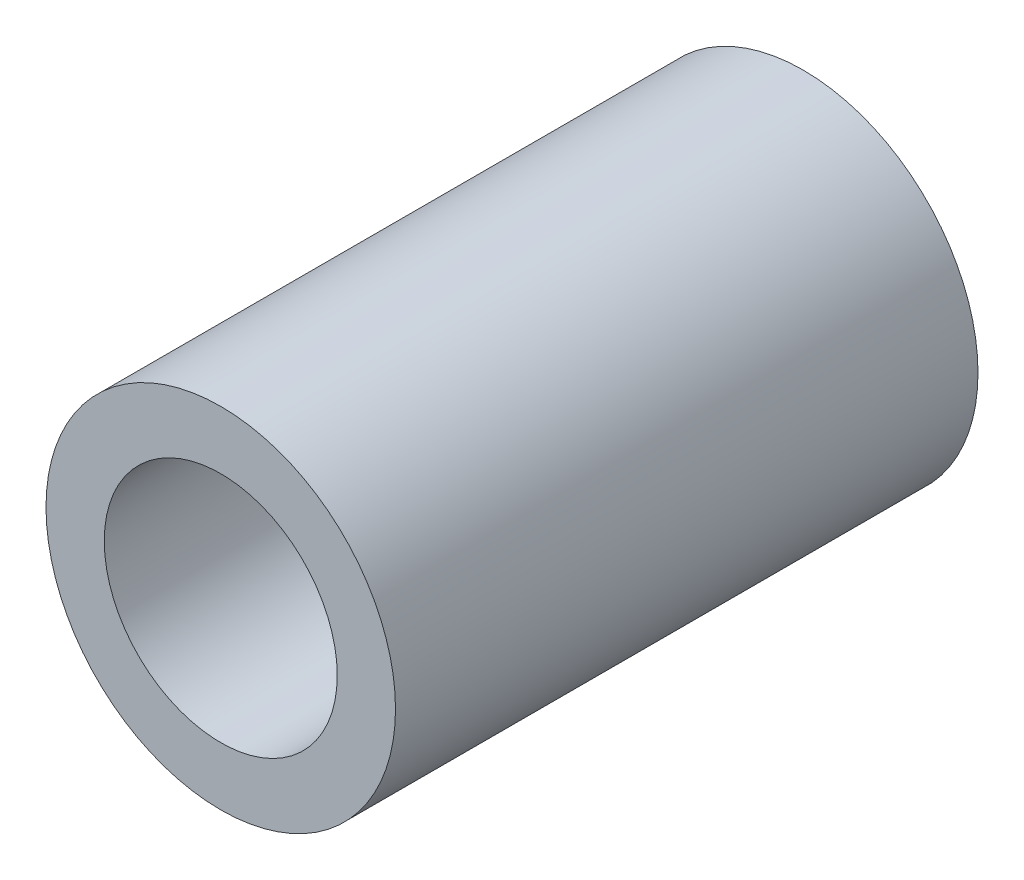
SolidWorks part; units mm, degrees
ref_plane "Front Plane" through (0, 0, 0) normal (0, 0, 1) x (1, 0, 0)
ref_plane "Top Plane" through (0, 0, 0) normal (0, 1, 0) x (1, 0, 0)
ref_plane "Right Plane" through (0, 0, 0) normal (1, 0, 0) x (0, 0, -1)
sketch "Sketch1" plane through (0, 0, 0) normal (0, 0, 1) x (1, 0, 0)
  circle A0 centre (0, 0) radius 15
  circle A1 centre (0, 0) radius 10
  dimension "D1" = 30
  dimension "D2" = 20
extrude "Boss-Extrude1" add sketch "Sketch1" along normal blind 50
